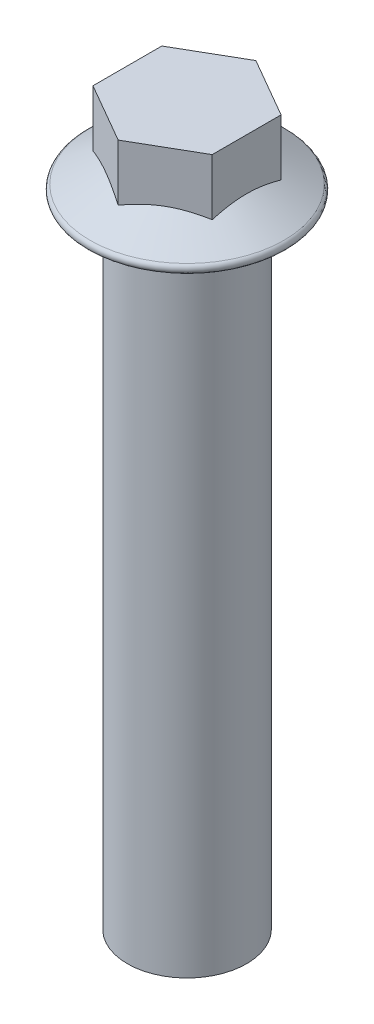
SolidWorks part; units mm, degrees
ref_plane "Front Plane" through (0, 0, 0) normal (0, 0, 1) x (1, 0, 0)
ref_plane "Top Plane" through (0, 0, 0) normal (0, 1, 0) x (1, 0, 0)
ref_plane "Right Plane" through (0, 0, 0) normal (1, 0, 0) x (0, 0, -1)
sketch "Sketch1" plane through (0, 0, 0) normal (0, 1, 0) x (1, 0, 0)
  circle A0 centre (0, 0) radius 6.35 construction
  circle A1 centre (0, 0) radius 9.525
  dimension "D1" = 12.7
  dimension "D2" = 19.05
extrude "Boss-Extrude1" add sketch "Sketch1" along normal blind 101.6
sketch "Sketch4" plane through (0, 101.6, 0) normal (0, 1, 0) x (1, 0, 0)
  line L0 (0, 10.9985) -> (9.525, 5.4993)
  line L1 (9.525, 5.4993) -> (9.525, -5.4993)
  line L2 (9.525, -5.4993) -> (0, -10.9985)
  line L3 (0, -10.9985) -> (-9.525, -5.4993)
  line L4 (-9.525, -5.4993) -> (-9.525, 5.4993)
  line L5 (-9.525, 5.4993) -> (0, 10.9985)
  point P5 (-9.525, 0)
  point P9 (9.525, 0)
  dimension "D1" = 19.05
  dimension "D2" = 19.05
extrude "Boss-Extrude2" add sketch "Sketch4" along normal blind 13.0969
sketch "Sketch5" plane through (0, 0, 0) normal (0, 0, 1) x (1, 0, 0)
  line L0 (0, 101.6) -> (-15.875, 101.6) construction
  line L1 (-4.7625, 101.6) -> (4.7625, 101.6) construction
  line L2 (0, 101.6) -> (-15.1083, 101.6)
  line L3 (-15.5052, 103.0812) -> (0, 112.0331)
  line L4 (0, 114.6969) -> (0, 101.6) construction
  line L5 (0, 101.6) -> (0, 112.0331)
  arc A0 (-15.1083, 101.6) -> (-15.5052, 103.0812) centre (-15.1083, 102.3938) cw
  point P9 (-15.875, 102.1883)
  dimension "D2" = 0.7937
  dimension "D1" = 15.875
  dimension "D3" = 30
revolve "Revolve2" add sketch "Sketch5" angle 360 about L5
hole_wizard "1/2-13 Tapped Hole1" positions "Sketch9" profile "Sketch10" tap size "1/2-13" standard "ANSI Inch"
sketch "Sketch9" plane through (0, 0, 0) normal (0, -1, 0) x (-1, 0, 0)
  point P0 (0, 0)
sketch "Sketch10" plane through (0, 0, 0) normal (1, 0, 0) x (0, 0, -1)
  line L0 (0, 0) -> (0, 28.6195)
  line L1 (0, 28.6195) -> (5.3581, 25.4)
  line L2 (5.3581, 25.4) -> (5.3581, 0)
  line L5 (5.3581, 0) -> (0, 0)
  line L10 (0, 28.6195) -> (-5.3581, 25.4) construction
  line L11 (0, -6.35) -> (0, 107.95) construction
  dimension "Tap Drill Dia." = 10.7163
  dimension "Tap Drill Depth" = 25.4
  dimension "Drill Angle" = 118
cosmetic thread "Hole Thread1" parameters "D1"=25.4, "D2"=12.7
